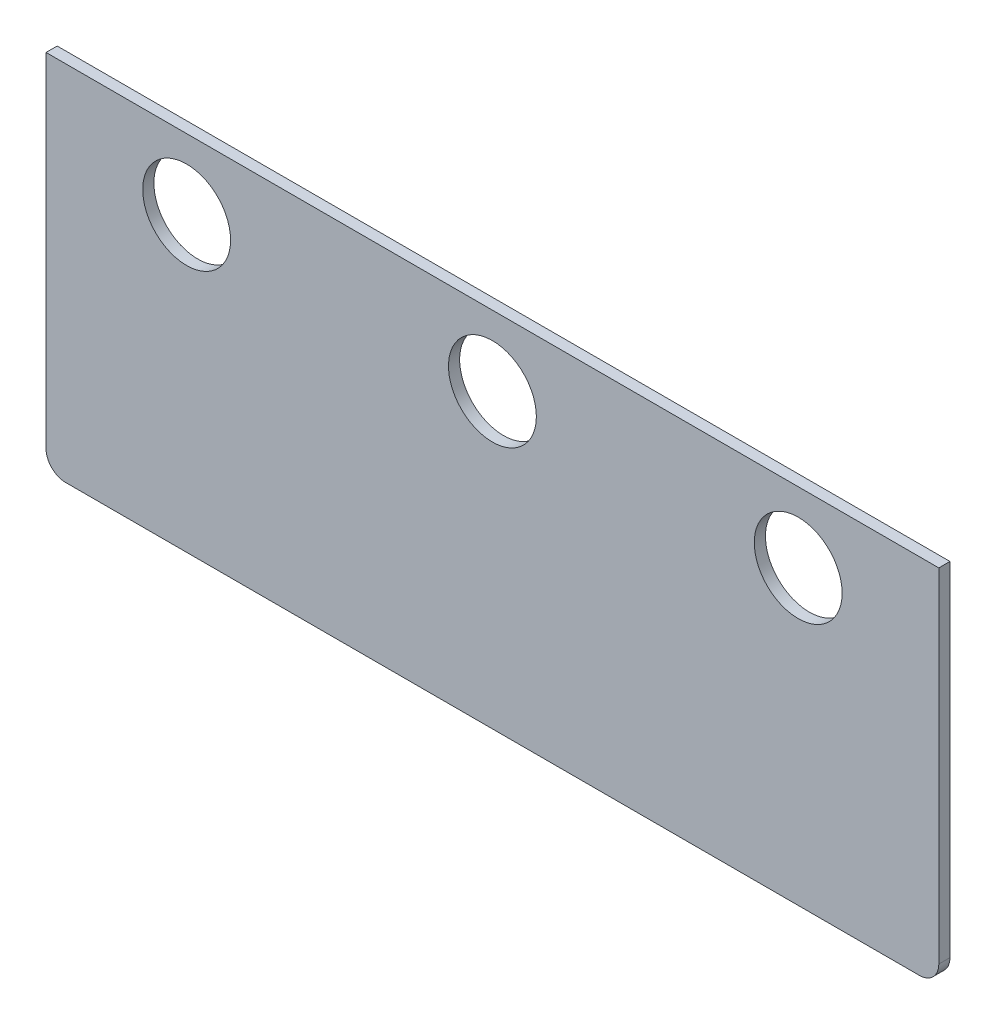
SolidWorks part; units mm, degrees
material "5052-H32"
ref_plane "Front Plane" through (0, 0, 0) normal (0, 0, 1) x (1, 0, 0)
ref_plane "Top Plane" through (0, 0, 0) normal (0, 1, 0) x (1, 0, 0)
ref_plane "Right Plane" through (0, 0, 0) normal (1, 0, 0) x (0, 0, -1)
sketch "Sketch1" plane through (0, 0, 0) normal (0, 0, 1) x (1, 0, 0)
  line L0 (-127, 103.175) -> (-127, 0)
  line L2 (127, 0) -> (127, 103.175)
  line L3 (127, 103.175) -> (-127, 103.175)
  line L4 (-127, 0) -> (127, 0)
  circle A0 centre (87, 83.175) radius 12.5
  circle A1 centre (-87, 83.175) radius 12.5
  circle A2 centre (0, 83.175) radius 12.5
  point P12 (0, 103.175)
  point P18 (0, 0)
  dimension "D1" = 103.175
  dimension "D2" = 254
  dimension "D3" = 20
  dimension "D5" = 40
  dimension "D6" = 40
extrude "Boss-Extrude1" add sketch "Sketch1" along normal blind 3.175
fillet "Fillet1" radius 5.5562 2 edges at (127, 0, 1.5875) (-127, 0, 1.5875)
equation "\"L\"= 420mm"
equation "\"W\"= 255mm"
equation "\"H\"= 110mm"
equation "\"Compartment Width\"= 80"
equation "\"T\"= 4.7625 * 2 / 3mm"
equation "\"Inside Fillet Radius\"= 5.55625mm"
equation "\"D1@Boss-Extrude1\"=\"T\""
equation "\"Hole\"=25mm"
equation "\"D4@Sketch1\"=\"Hole\""
equation "\"D2@Sketch1\"=\"W\"-1"
equation "\"D1@Sketch1\"=\"H\"+\"T\"-10"
equation "\"Offset\"= 18mm"
equation "\"Wheel to Wall\"= 43"
equation "\"D1@Fillet1\"=\"Inside Fillet Radius\""
